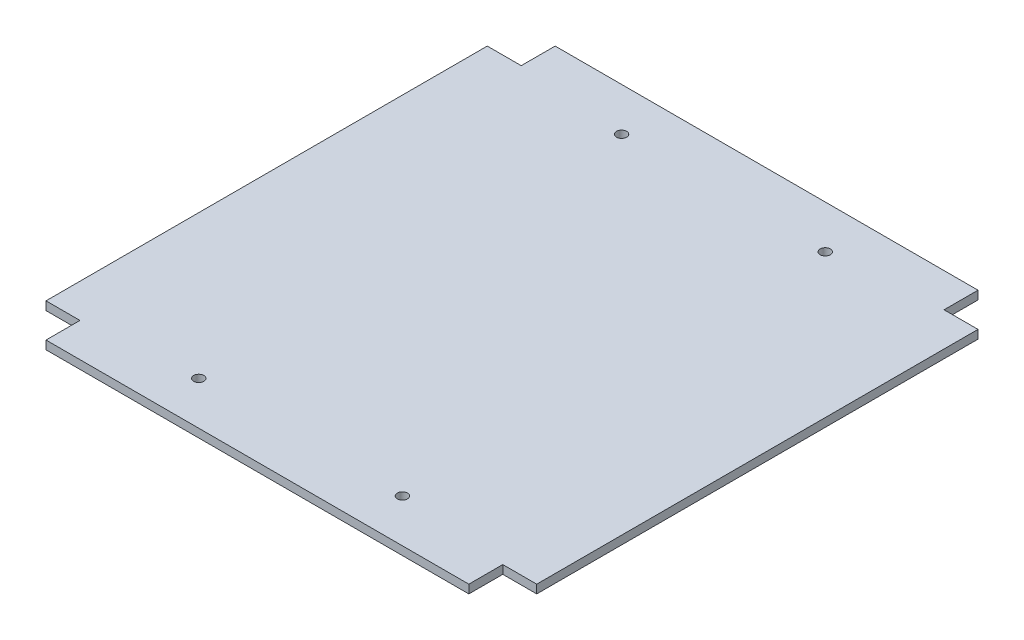
SolidWorks part; units mm, degrees
ref_plane "Plan de face" through (0, 0, 0) normal (0, 0, 1) x (1, 0, 0)
ref_plane "Plan de dessus" through (0, 0, 0) normal (0, 1, 0) x (1, 0, 0)
ref_plane "Plan de droite" through (0, 0, 0) normal (1, 0, 0) x (0, 0, -1)
sketch "Esquisse1" plane through (0, 0, 0) normal (0, 1, 0) x (1, 0, 0)
  line L0 (-174.5839, 0) -> (222.3951, 0) construction
  line L1 (-144.5683, 40) -> (-104.5683, 40)
  line L2 (-104.5683, 40) -> (-104.5683, -40)
  line L3 (-144.5683, -40) -> (-104.5683, -40)
  line L4 (0, 143.2846) -> (0, -128.3979) construction
  line L5 (144.5683, -40) -> (104.5683, -40)
  line L6 (104.5683, 40) -> (104.5683, -40)
  line L7 (144.5683, 40) -> (104.5683, 40)
  line L8 (-144.5683, 40) -> (-144.5683, 150)
  line L9 (-144.5683, 150) -> (144.5683, 150)
  line L10 (144.5683, 150) -> (144.5683, 40)
  line L11 (144.5683, -40) -> (144.5683, -150)
  line L12 (144.5683, -150) -> (-144.5683, -150)
  line L13 (-144.5683, -150) -> (-144.5683, -40)
  line L14 (-144.5683, 130) -> (-124.5683, 130)
  line L15 (-124.5683, 130) -> (-124.5683, 150)
  line L16 (144.5683, 130) -> (124.5683, 130)
  line L17 (124.5683, 130) -> (124.5683, 150)
  line L18 (124.5683, -130) -> (124.5683, -150)
  line L19 (144.5683, -130) -> (124.5683, -130)
  line L20 (-124.5683, -130) -> (-124.5683, -150)
  line L21 (-144.5683, -130) -> (-124.5683, -130)
  line L22 (-144.5683, 40) -> (-144.5683, -40)
  line L23 (144.5683, 40) -> (144.5683, -40)
  circle A0 centre (0, 0) radius 150
  circle A1 centre (-60, 124.57) radius 3
  circle A4 centre (60, 124.57) radius 3
  circle A5 centre (60, -124.57) radius 3
  circle A6 centre (-60, -124.57) radius 3
  point P9 (-104.5683, 0)
  point P40 (-150, 0)
  dimension "D1" = 300
  dimension "D4" = 6
  dimension "D5" = 120
  dimension "D2" = 40
  dimension "D3" = 40
  dimension "D6" = 25.43
  dimension "D10" = 20
  dimension "D11" = 20
extrude "Boss.-Extru.1" add sketch "Esquisse1" along normal blind 5 contours A0 L9 L15 L14 L8 | L7 A0 L1 L2 L3 L5 L6 A6 A5 A1 A4 | A0 L13 L21 L20 L12 | A0 L12 L18 L19 L11 | A0 L10 L16 L17 L9 | L1 L22 L3 L2 | L23 L7 L6 L5
